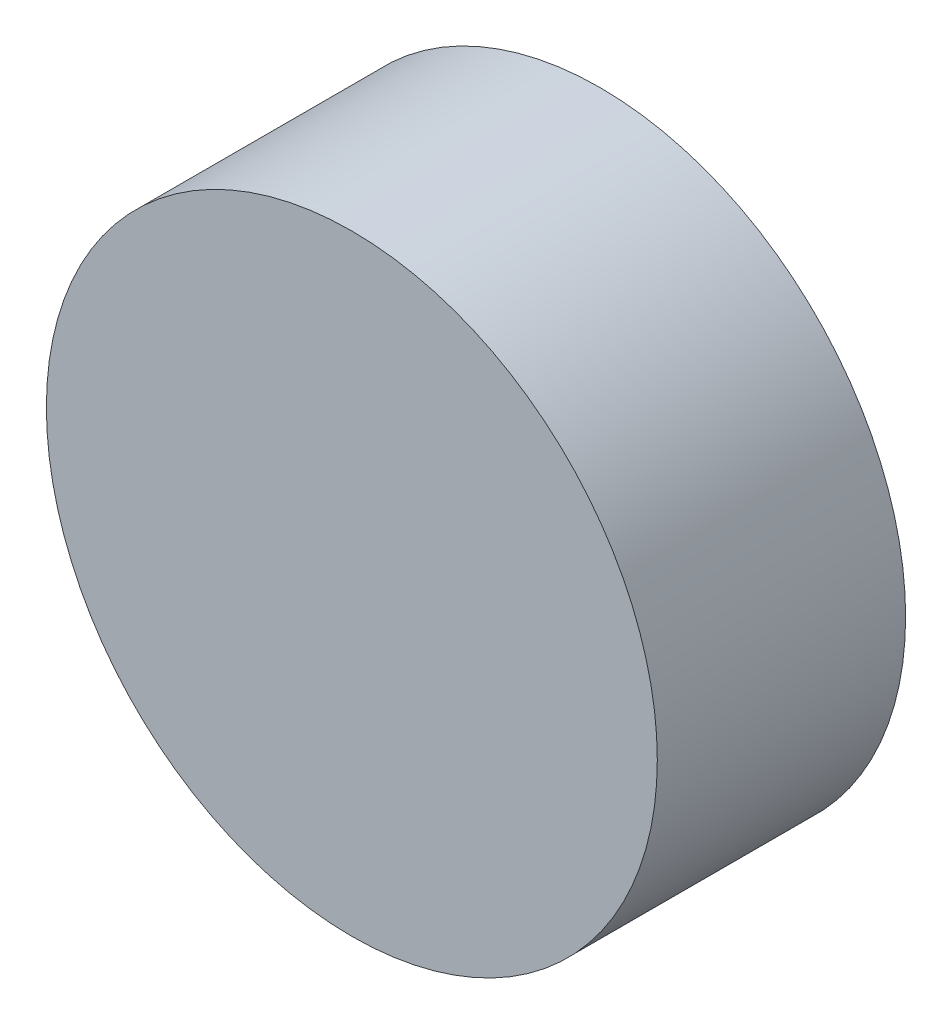
SolidWorks part; units mm, degrees
ref_plane "Front Plane" through (0, 0, 0) normal (0, 0, 1) x (1, 0, 0)
ref_plane "Top Plane" through (0, 0, 0) normal (0, 1, 0) x (1, 0, 0)
ref_plane "Right Plane" through (0, 0, 0) normal (1, 0, 0) x (0, 0, -1)
sketch "Sketch1" plane through (0, 0, 0) normal (0, 0, 1) x (1, 0, 0)
  circle A0 centre (0, 0) radius 3.875
  dimension "D1" = 7.75
extrude "Boss-Extrude1" add sketch "Sketch1" against normal blind 3.15
shell "Shell1" thickness 1.45
